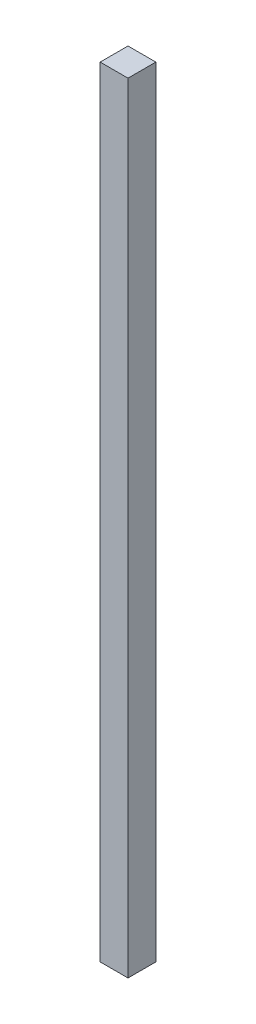
SolidWorks part; units mm, degrees
material "Thornel Mat VMA"
ref_plane "前视基准面" through (0, 0, 0) normal (0, 0, 1) x (1, 0, 0)
ref_plane "上视基准面" through (0, 0, 0) normal (0, 1, 0) x (1, 0, 0)
ref_plane "右视基准面" through (0, 0, 0) normal (1, 0, 0) x (0, 0, -1)
other "Configuration Table"
sketch "草图1" plane through (0, 0, 0) normal (0, 1, 0) x (1, 0, 0)
  line L1 (-5, -5) -> (5, -5)
  line L2 (-5, -5) -> (-5, 5)
  line L3 (-5, 5) -> (5, 5)
  line L4 (5, -5) -> (5, 5)
  line L5 (-5, -5) -> (5, 5) construction
  line L6 (-5, 5) -> (5, -5) construction
  point P0 (0, 0)
extrude "凸台-拉伸1" add sketch "草图1" along normal blind 280
